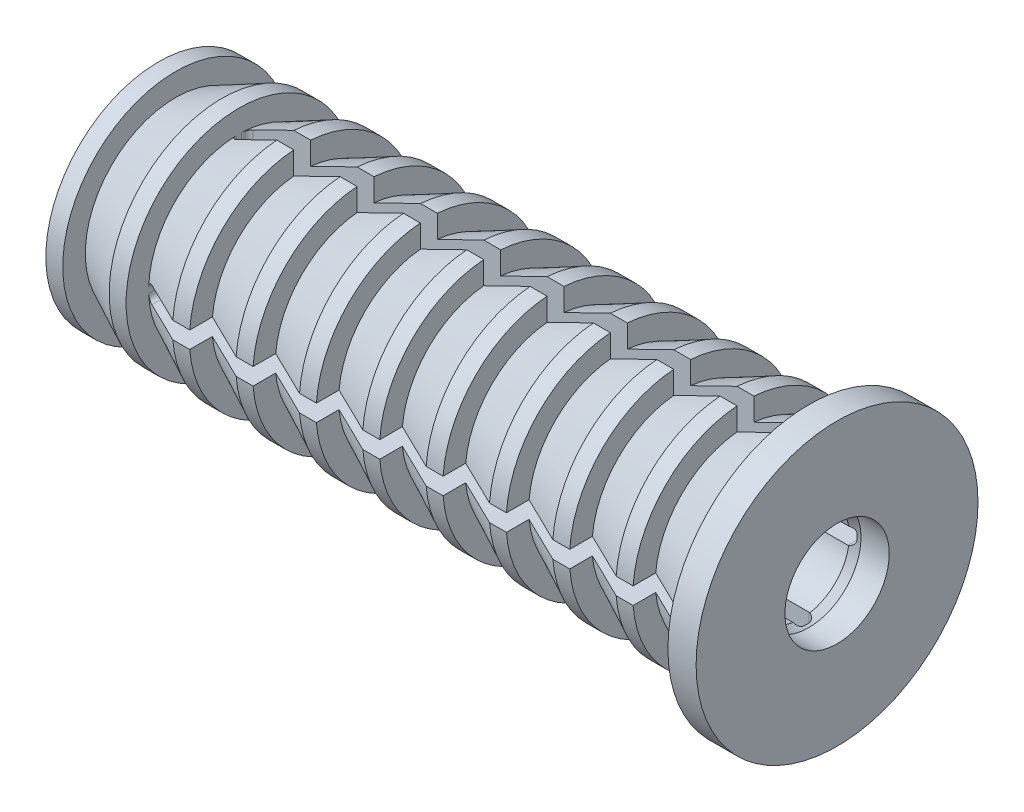
SolidWorks part; units mm, degrees
material "Nylon 101"
ref_plane "Front Plane" through (0, 0, 0) normal (0, 0, 1) x (1, 0, 0)
ref_plane "Top Plane" through (0, 0, 0) normal (0, 1, 0) x (1, 0, 0)
ref_plane "Right Plane" through (0, 0, 0) normal (1, 0, 0) x (0, 0, -1)
sketch "Sketch2" plane through (0, 0, 0) normal (0, 0, 1) x (1, 0, 0)
  line L0 (-12, 1) -> (-11.5337, 2)
  line L1 (-11.2337, 1.6) -> (-11.2337, 2)
  line L2 (-11.2337, 2) -> (-11.5337, 2)
  line L3 (-11.2337, 1.6) -> (-10.4103, 2)
  line L4 (-10.4103, 2) -> (-10.1103, 2)
  line L5 (-10.1103, 2) -> (-10.1103, 1.6)
  line L6 (-10.1103, 1.6) -> (-9.287, 2)
  line L7 (-9.287, 2) -> (-8.987, 2)
  line L8 (-8.987, 2) -> (-8.987, 1.6)
  line L9 (-8.987, 1.6) -> (-8.1636, 2)
  line L10 (-8.1636, 2) -> (-7.8636, 2)
  line L11 (-7.8636, 2) -> (-7.8636, 1.6)
  line L12 (-7.8636, 1.6) -> (-7.0402, 2)
  line L13 (-7.0402, 2) -> (-6.7402, 2)
  line L14 (-6.7402, 2) -> (-6.7402, 1.6)
  line L15 (-6.7402, 1.6) -> (-5.9168, 2)
  line L16 (-5.9168, 2) -> (-5.6168, 2)
  line L17 (-5.6168, 2) -> (-5.6168, 1.6)
  line L18 (-5.6168, 1.6) -> (-4.7935, 2)
  line L19 (-4.7935, 2) -> (-4.4935, 2)
  line L20 (-4.4935, 2) -> (-4.4935, 1.6)
  line L21 (-4.4935, 1.6) -> (-3.6701, 2)
  line L22 (-3.6701, 2) -> (-3.3701, 2)
  line L23 (-3.3701, 2) -> (-3.3701, 1.6)
  line L24 (-3.3701, 1.6) -> (-2.5467, 2)
  line L25 (-2.5467, 2) -> (-2.2467, 2)
  line L26 (-2.2467, 2) -> (-2.2467, 1.6)
  line L27 (-2.2467, 1.6) -> (-1.4234, 2)
  line L28 (-1.4234, 2) -> (-1.1234, 2)
  line L29 (-1.1234, 2) -> (-1.1234, 1.6)
  line L30 (-1.1234, 1.6) -> (-0.3, 2)
  line L31 (-0.3, 2) -> (0, 2)
  line L32 (0, 2) -> (0, 2.5)
  line L34 (-11.7402, 0.85) -> (-0.1299, 0.85)
  line L35 (0, 0) -> (-12, 0) construction
  line L36 (0, 2.5) -> (0.5, 2.5)
  line L37 (-0.1299, 0.85) -> (0, 0.925)
  line L38 (0, 0.925) -> (0.5, 0.925)
  line L39 (0.5, 0.925) -> (0.5, 2.5)
  line L40 (-12, 1) -> (-11.7402, 0.85)
  dimension "D1" = 0.3
  dimension "D2" = 65
  dimension "D3" = 12
  dimension "D4" = 2
  dimension "D5" = 0.4
  dimension "D6" = 0.85
  dimension "D7" = 0.925
  dimension "D8" = 0.5
  dimension "D9" = 2.5
  dimension "D10" = 30
  dimension "D12" = 30
  dimension "D13" = 1
revolve "Revolve2" add sketch "Sketch2" angle 360 about L35
sketch "Sketch4" plane through (0, 0, 0) normal (0, 1, 0) x (1, 0, 0)
  line L1 (-10.0103, -0.15) -> (-0.1433, -0.15)
  line L2 (-10.1103, -0.05) -> (-10.1103, 0.05)
  line L3 (-10.0103, 0.15) -> (-0.1433, 0.15)
  line L4 (-0.0433, -0.05) -> (-0.0433, 0.05)
  line L5 (-10.1103, -2) -> (-10.1103, 2) construction
  line L6 (-0.0433, 0.9) -> (-0.0433, -0.9) construction
  line L10 (0, 0.925) -> (-0.1299, 0.85) construction
  line L11 (-0.1299, -0.85) -> (0, -0.925) construction
  arc A0 (-0.1433, 0.15) -> (-0.0433, 0.05) centre (-0.1433, 0.05) cw
  arc A1 (-0.1433, -0.15) -> (-0.0433, -0.05) centre (-0.1433, -0.05) ccw
  arc A2 (-10.1103, -0.05) -> (-10.0103, -0.15) centre (-10.0103, -0.05) ccw
  arc A3 (-10.1103, 0.05) -> (-10.0103, 0.15) centre (-10.0103, 0.05) cw
  point P6 (-10.1103, 0)
  point P12 (-0.0433, 0.15)
  point P15 (-0.0433, -0.15)
  point P23 (-0.0433, 0)
  dimension "D2" = 0.1
  dimension "D1" = 0.3
  dimension "D3" = 1.8
extrude "Cut-Extrude2" cut sketch "Sketch4" against normal through all and the other way through all
sketch "Sketch5" plane through (0, 0, 0) normal (0, 0, 1) x (1, 0, 0)
  line L0 (-10.1103, -2) -> (-10.1103, 2) construction
  line L1 (-0.1433, -0.15) -> (-10.0103, -0.15)
  line L2 (-0.0433, -0.05) -> (-0.0433, 0.05)
  line L3 (-0.1433, 0.15) -> (-10.0103, 0.15)
  line L4 (-10.1103, -0.05) -> (-10.1103, 0.05)
  line L8 (-0.0433, -0.9) -> (-0.0433, 0.9) construction
  line L9 (-0.0433, -0.9) -> (0, -0.925) construction
  line L10 (0, 0.925) -> (-0.0433, 0.9) construction
  arc A0 (-0.1433, 0.15) -> (-0.0433, 0.05) centre (-0.1433, 0.05) cw
  arc A1 (-0.0433, -0.05) -> (-0.1433, -0.15) centre (-0.1433, -0.05) cw
  arc A2 (-10.0103, -0.15) -> (-10.1103, -0.05) centre (-10.0103, -0.05) cw
  arc A3 (-10.0103, 0.15) -> (-10.1103, 0.05) centre (-10.0103, 0.05) ccw
  point P4 (-0.0433, 0)
  point P12 (-0.0433, -0.15)
  point P15 (-10.1103, -0.15)
  point P18 (-10.1103, 0.15)
  dimension "D2" = 0.1
  dimension "D1" = 0.3
  dimension "D3" = 1.8
extrude "Cut-Extrude3" cut sketch "Sketch5" against normal through all and the other way through all
